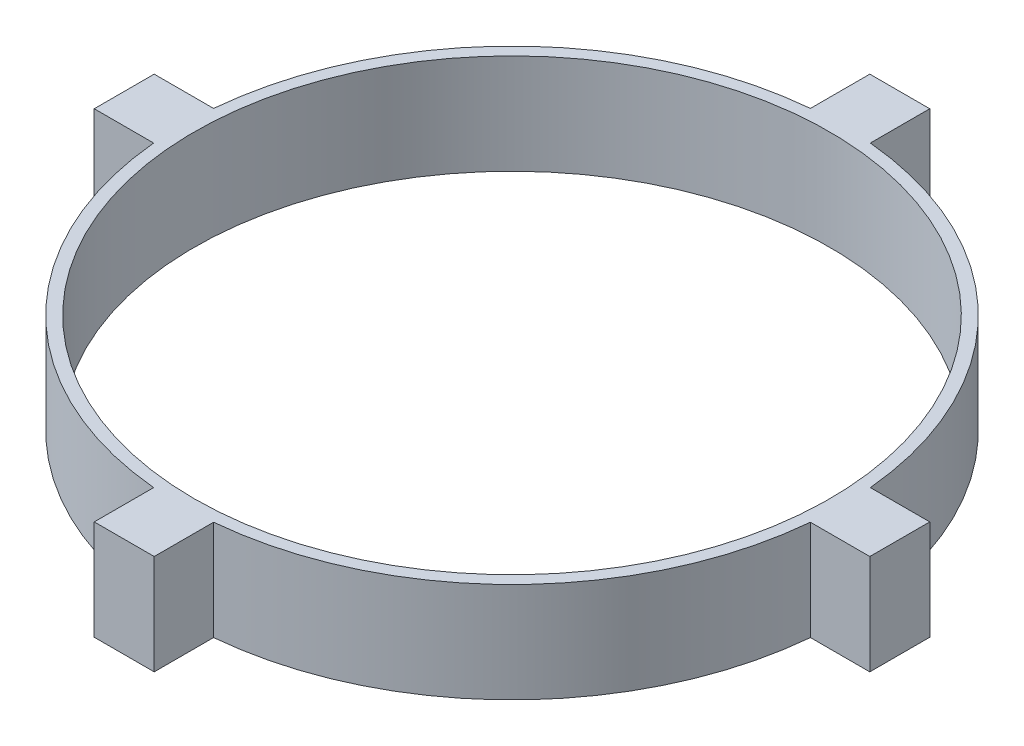
SolidWorks part; units mm, degrees
ref_plane "Front Plane" through (0, 0, 0) normal (0, 0, 1) x (1, 0, 0)
ref_plane "Top Plane" through (0, 0, 0) normal (0, 1, 0) x (1, 0, 0)
ref_plane "Right Plane" through (0, 0, 0) normal (1, 0, 0) x (0, 0, -1)
sketch "Sketch1" plane through (0, 0, 0) normal (0, 1, 0) x (1, 0, 0)
  circle A1 centre (0, 0) radius 42.9384
extrude "Boss-Extrude1" add sketch "Sketch1" along normal blind 12.7
sketch "Sketch2" plane through (0, 0, 0) normal (0, 0, 1) x (1, 0, 0)
  line L1 (-42.9384, 12.7) -> (-49.2884, 12.7)
  line L5 (42.9384, 12.7) -> (-42.9384, 12.7) construction
  line L6 (-42.0241, 12.7) -> (-42.9384, 12.7)
  line L7 (-42.0241, 5.5435) -> (-49.2884, 12.7)
  line L8 (-42.0241, 12.7) -> (-42.0241, 5.5435)
sketch "Sketch4" plane through (0, 0, 0) normal (0, 0, 1) x (1, 0, 0)
  circle A0 centre (0, 3.2871) radius 1.6929
sketch "Sketch6" plane through (0, 0, 0) normal (0, 0, 1) x (1, 0, 0)
  line L10 (0, 0) -> (0, 8.6868)
  line L14 (42.5405, 0) -> (49.2884, 0)
  line L15 (42.5405, 0) -> (42.5405, 12.7)
  line L16 (42.5405, 12.7) -> (49.2884, 12.7)
  line L17 (49.2884, 0) -> (49.2884, 12.7)
extrude "Boss-Extrude2" add sketch "Sketch6" along normal blind 3.81 and the other way blind 3.81 contours L15 L14 L17 L16
pattern_circular "CirPattern8" count 4 over 360 about axis through (0, 0, 0) along (0, 1, 0) of "Boss-Extrude2"
sketch "Sketch8" plane through (0, 12.7, 0) normal (0, 1, 0) x (1, 0, 0)
  line L0 (-42.769, 3.81) -> (-41.7365, 3.81)
  line L1 (-42.769, -3.81) -> (-41.7365, -3.81)
  line L2 (-3.81, -42.769) -> (-3.81, -41.7365)
  line L3 (3.81, -42.769) -> (3.81, -41.7365)
  line L4 (42.769, -3.81) -> (41.7365, -3.81)
  line L5 (42.769, 3.81) -> (41.7365, 3.81)
  line L6 (3.81, 42.769) -> (3.81, 41.7365)
  line L7 (-3.81, 42.769) -> (-3.81, 41.7365)
  circle A1 centre (0, 0) radius 41.91
  circle A2 centre (0, 0) radius 42.9384
  arc M4 (-42.769, -3.81) -> (-3.81, -42.769) centre (0, 0) ccw
  arc M8 (3.81, -42.769) -> (42.769, -3.81) centre (0, 0) ccw
  arc M12 (42.769, 3.81) -> (3.81, 42.769) centre (0, 0) ccw
  arc M16 (-3.81, 42.769) -> (-42.769, 3.81) centre (0, 0) ccw
extrude "Cut-Extrude3" cut sketch "Sketch8" against normal blind 24 contours A1 L1 L2 M4 | A1 L3 L4 M8 | A1 L5 L6 M12 | A1 L7 L0 M16
sketch "Sketch10" plane through (0, 12.7, 0) normal (0, 1, 0) x (1, 0, 0)
  circle A0 centre (0, 0) radius 40.386
extrude "Cut-Extrude4" cut sketch "Sketch10" against normal blind 38.1
sketch "Sketch11" plane through (0, 12.7, 0) normal (0, 1, 0) x (1, 0, 0)
  circle A0 centre (0, 0) radius 41.91
  circle A2 centre (0, 0) radius 39.37
